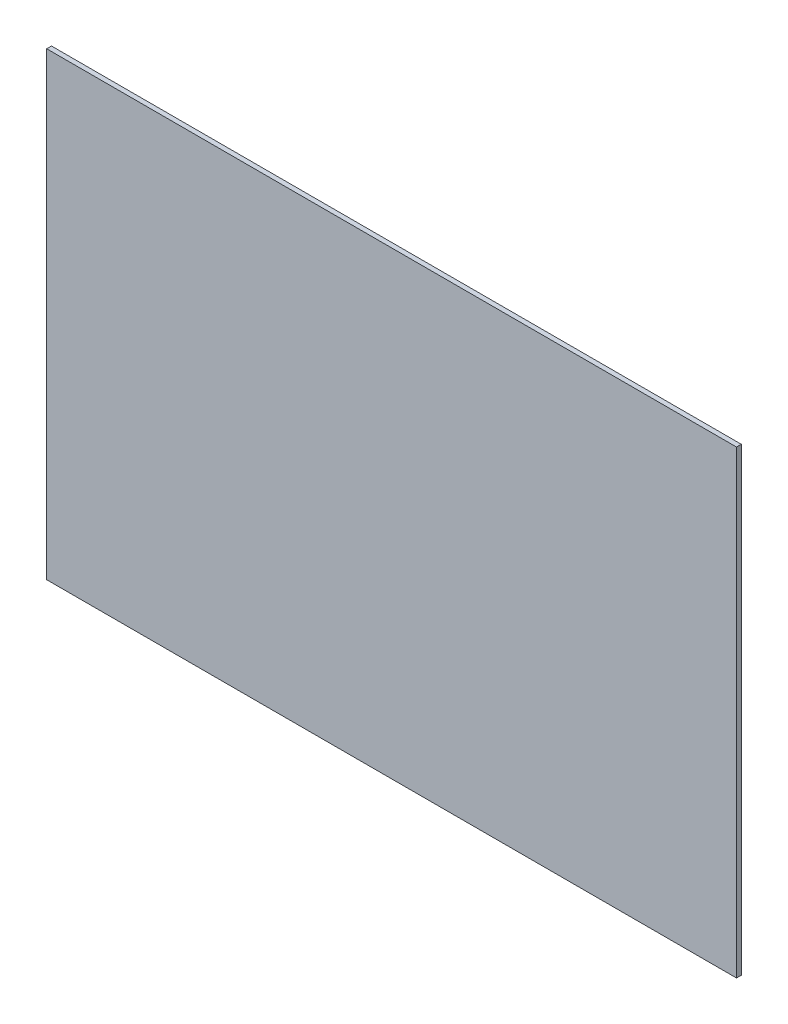
SolidWorks part; units mm, degrees
material "Custom Plastic"
ref_plane "X-Y Datum" through (0, 0, 0) normal (0, 0, 1) x (1, 0, 0)
ref_plane "X-Z Datum" through (0, 0, 0) normal (0, 1, 0) x (1, 0, 0)
ref_plane "Y-Z Datum" through (0, 0, 0) normal (1, 0, 0) x (0, 0, -1)
sketch "Sketch2" plane through (0, 0, 0) normal (0, 0, 1) x (1, 0, 0)
  line L1 (-457.2, 304.8) -> (457.2, 304.8)
  line L2 (-457.2, 304.8) -> (-457.2, -304.8)
  line L3 (-457.2, -304.8) -> (457.2, -304.8)
  line L4 (457.2, 304.8) -> (457.2, -304.8)
  line L5 (-457.2, 304.8) -> (457.2, -304.8) construction
  line L6 (-457.2, -304.8) -> (457.2, 304.8) construction
  point P0 (0, 0)
  dimension "D1" = 914.4
  dimension "D2" = 609.6
extrude "Boss-Extrude1" add sketch "Sketch2" along normal blind 6.35
